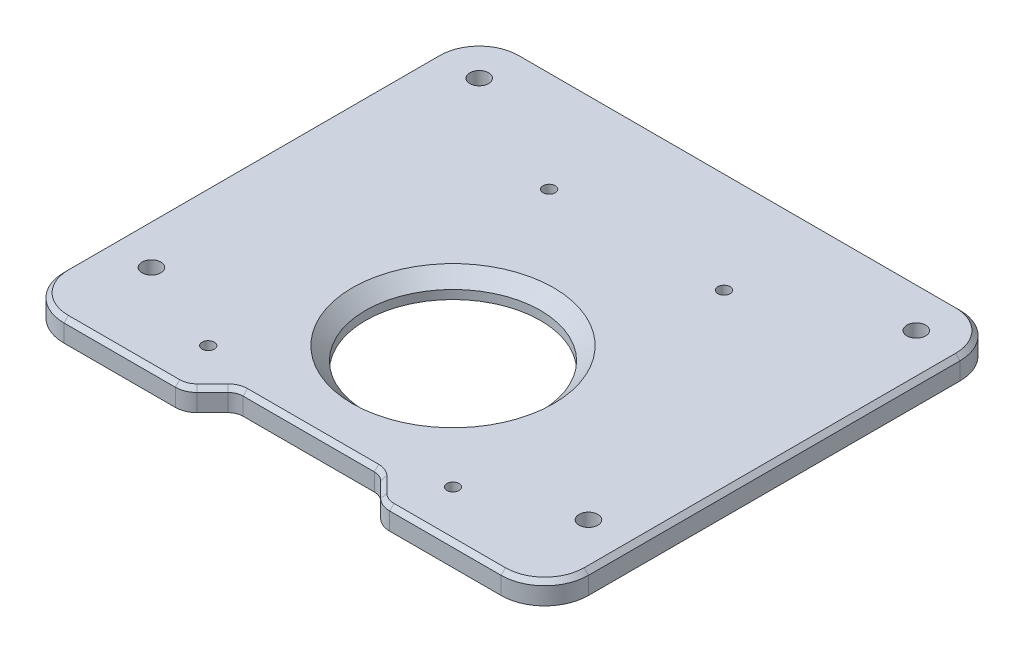
SolidWorks part; units mm, degrees
ref_plane "Front Plane" through (0, 0, 0) normal (0, 0, 1) x (1, 0, 0)
ref_plane "Top Plane" through (0, 0, 0) normal (0, 1, 0) x (1, 0, 0)
ref_plane "Right Plane" through (0, 0, 0) normal (1, 0, 0) x (0, 0, -1)
sketch "Sketch1" plane through (0, 0, 0) normal (0, 1, 0) x (1, 0, 0)
  line L0 (0, 0) -> (0, -28) construction
  line L1 (0, -28) -> (-28, -28) construction
  line L2 (0, -28) -> (28, -28) construction
  line L3 (0, 0) -> (0, 42) construction
  line L4 (0, 42) -> (20, 42) construction
  line L5 (0, 42) -> (-20, 42) construction
  line L6 (-15, -36.5) -> (15, -36.5) construction
  line L7 (-15, -34.85) -> (15, -34.85)
  line L8 (-15, -38.15) -> (15, -38.15)
  line L9 (0, 0) -> (0, -36.5) construction
  circle A0 centre (0, 0) radius 35 construction
  circle A1 centre (28, -28) radius 1.4
  circle A2 centre (-28, -28) radius 1.4
  circle A3 centre (-20, 42) radius 1.4
  circle A4 centre (20, 42) radius 1.4
  arc A5 (-15, -34.85) -> (-15, -38.15) centre (-15, -36.5) ccw
  arc A6 (15, -38.15) -> (15, -34.85) centre (15, -36.5) ccw
  point P15 (0, -36.5)
  dimension "D1" = 70
  dimension "D6" = 2.8
  dimension "D9" = 1.65
  dimension "D2" = 28
  dimension "D3" = 42
  dimension "D4" = 56
  dimension "D5" = 40
  dimension "D7" = 30
  dimension "D8" = 36.5
sketch "Sketch2" plane through (0, 0, 0) normal (0, 1, 0) x (1, 0, 0)
  line L0 (0, 0) -> (0, 66) construction
  line L1 (-60, 66) -> (60, 66)
  line L2 (-60, 66) -> (-60, -39)
  line L4 (60, 66) -> (60, -39)
  line L6 (-60, -39) -> (60, -39)
  circle A0 centre (-28, -28) radius 1.4 construction
  circle A1 centre (28, -28) radius 1.4 construction
  circle A2 centre (20, 42) radius 1.4 construction
  circle A3 centre (-20, 42) radius 1.4 construction
  circle A4 centre (-28, -28) radius 1.4
  circle A5 centre (28, -28) radius 1.4
  circle A6 centre (20, 42) radius 1.4
  circle A7 centre (-20, 42) radius 1.4
  dimension "D1" = 120
  dimension "D2" = 105
  dimension "D3" = 66
extrude "Boss-Extrude2" add sketch "Sketch2" along normal blind 5
sketch "Sketch9" plane through (0, 5, 0) normal (0, 1, 0) x (1, 0, 0)
  line L0 (-15, -36.5) -> (15, -36.5) construction
  line L1 (-15, -33) -> (15, -33) construction
  line L2 (-15, -40) -> (15, -40) construction
  line L3 (-17.4749, -34.0251) -> (-23.4497, -40)
  line L4 (-23.4497, -40) -> (23.4497, -40)
  line L5 (23.4497, -40) -> (17.4749, -34.0251)
  line L6 (-15, -33) -> (15, -33)
  arc A0 (-15, -33) -> (-15, -40) centre (-15, -36.5) ccw construction
  arc A1 (15, -40) -> (15, -33) centre (15, -36.5) ccw construction
  arc A2 (-17.4749, -34.0251) -> (-15, -33) centre (-15, -36.5) cw
  arc A3 (15, -33) -> (17.4749, -34.0251) centre (15, -36.5) cw
  point P2 (0, -36.5)
  point P17 (-21.2391, -40)
  point P18 (21.7266, -40)
  dimension "D1" = 3.5
  dimension "D2" = 45
extrude "Cut-Extrude7" cut sketch "Sketch9" against normal through all
fillet "Fillet5" radius 10 4 edges at (-60, 2.5, -66) (60, 2.5, -66) (60, 2.5, 39) (-60, 2.5, 39)
sketch "Sketch10" plane through (0, 0, 0) normal (0, 1, 0) x (1, 0, 0)
  circle A0 centre (0, 0) radius 20
  dimension "D1" = 40
extrude "Cut-Extrude9" cut sketch "Sketch10" along normal through all
chamfer "Chamfer3" distance 3 angle 45 1 edges at (0, 5, 20)
fillet "Fillet6" radius 5 2 edges at (-22.4497, 2.5, 39) (22.4497, 2.5, 39)
chamfer "Chamfer4" distance 1 angle 45 16 edges at (-19.2301, 5, 35.7803) (-16.3394, 5, 33.2664) (-22.6074, 5, 38.6194) (0, 5, 33) (-37.2604, 5, 39) (16.3394, 5, 33.2664) (-57.0711, 5, 36.0711) (19.2301, 5, 35.7803) (-60, 5, -13.5) (22.6074, 5, 38.6194) (-57.0711, 5, -63.0711) (37.2604, 5, 39) (0, 5, -66) (57.0711, 5, 36.0711) (57.0711, 5, -63.0711) (60, 5, -13.5)
sketch "Sketch11" plane through (0, 5, 0) normal (0, 1, 0) x (1, 0, 0)
  line L0 (0, 0) -> (0, 42) construction
  line L1 (50, -19) -> (-50, -19) construction
  line L2 (50, -19) -> (50, 56) construction
  line L3 (50, 56) -> (-50, 56) construction
  line L4 (-50, -19) -> (-50, 56) construction
  line L5 (50, -19) -> (-50, 56) construction
  line L6 (50, 56) -> (-50, -19) construction
  circle A0 centre (-50, 56) radius 2.15
  circle A1 centre (50, 56) radius 2.15
  circle A2 centre (-50, -19) radius 2.15
  circle A3 centre (50, -19) radius 2.15
  point P0 (0, 18.5)
  dimension "D4" = 4.3
  dimension "D1" = 100
  dimension "D2" = 56
  dimension "D3" = 75
extrude "Cut-Extrude10" cut sketch "Sketch11" against normal through all
sketch "Sketch13" plane through (0, 0, 0) normal (0, -1, 0) x (1, 0, 0)
  circle A0 centre (-28, 28) radius 3.25
  circle A1 centre (28, 28) radius 3.25
  circle A2 centre (-20, -42) radius 3.25
  circle A3 centre (20, -42) radius 3.25
  dimension "D1" = 6.5
extrude "Cut-Extrude12" cut sketch "Sketch13" against normal blind 2.5
